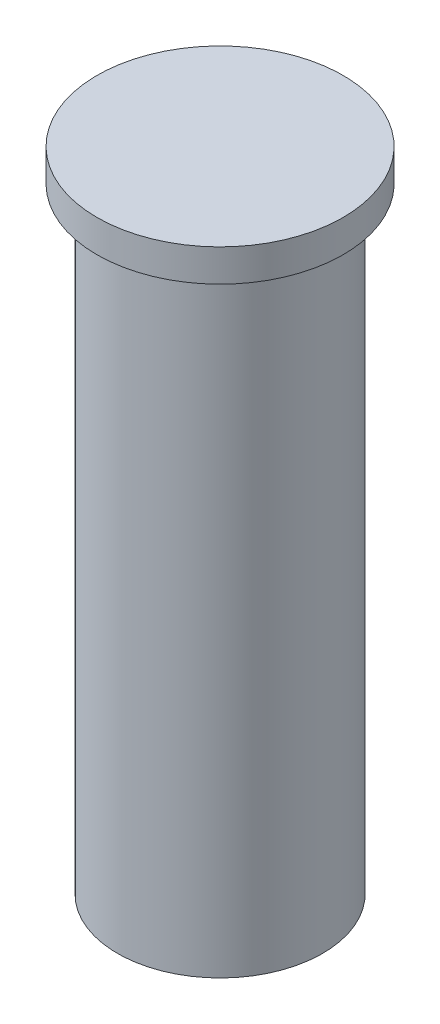
SolidWorks part; units mm, degrees
ref_plane "Front Plane" through (0, 0, 0) normal (0, 0, 1) x (1, 0, 0)
ref_plane "Top Plane" through (0, 0, 0) normal (0, 1, 0) x (1, 0, 0)
ref_plane "Right Plane" through (0, 0, 0) normal (1, 0, 0) x (0, 0, -1)
sketch "Sketch1" plane through (0, 0, 0) normal (0, 1, 0) x (1, 0, 0)
  circle A0 centre (0, 0) radius 6.35
extrude "Boss-Extrude1" add sketch "Sketch1" along normal blind 38.1
sketch "Sketch3" plane through (0, 38.1, 0) normal (0, 1, 0) x (1, 0, 0)
  circle A0 centre (0, 0) radius 7.62
extrude "Boss-Extrude2" add sketch "Sketch3" along normal blind 2
